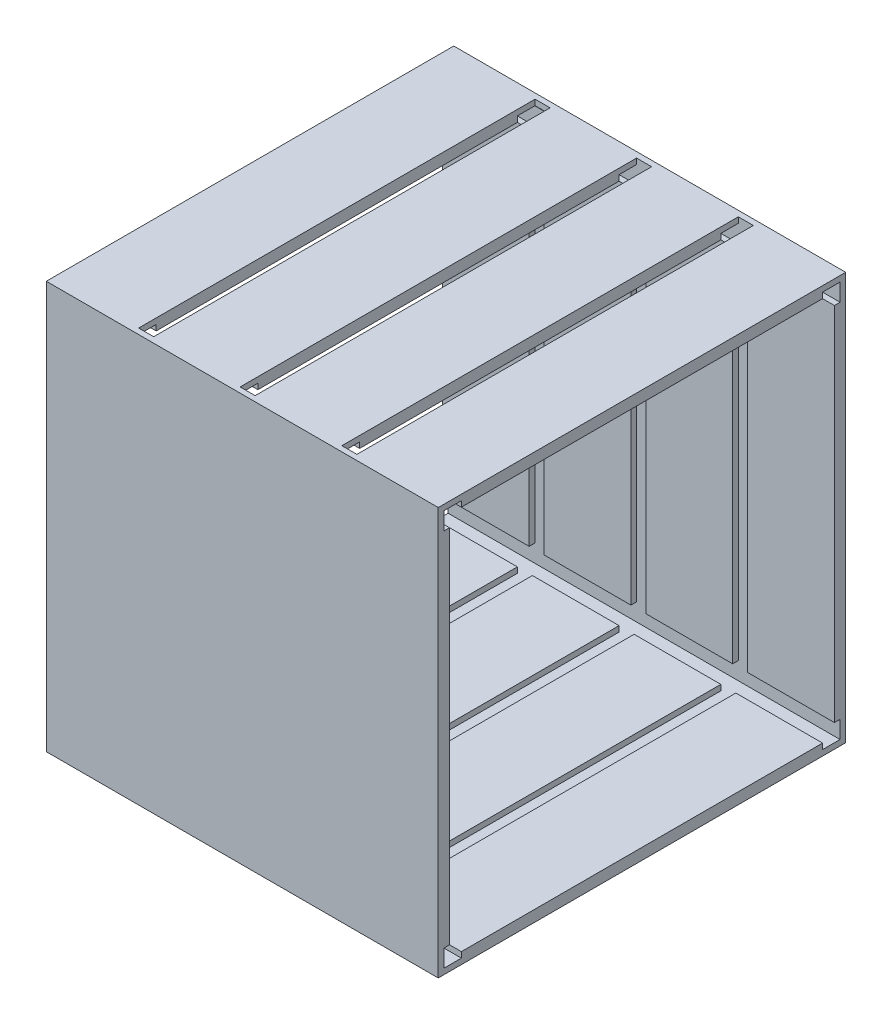
SolidWorks part; units mm, degrees
ref_plane "Front Plane" through (0, 0, 0) normal (0, 0, 1) x (1, 0, 0)
ref_plane "Top Plane" through (0, 0, 0) normal (0, 1, 0) x (1, 0, 0)
ref_plane "Right Plane" through (0, 0, 0) normal (1, 0, 0) x (0, 0, -1)
sketch "Sketch1" plane through (0, 0, 0) normal (1, 0, 0) x (0, 0, -1)
  line L1 (0, 0) -> (688.1, 0)
  line L2 (0, 0) -> (0, 688.1)
  line L3 (0, 688.1) -> (688.1, 688.1)
  line L4 (688.1, 0) -> (688.1, 688.1)
  line L5 (0, 0) -> (19.05, 0) construction
  line L6 (0, 0) -> (0, 19.05) construction
  line L7 (0, 19.05) -> (19.05, 19.05) construction
  line L8 (19.05, 0) -> (19.05, 19.05) construction
  line L9 (19.05, 19.05) -> (669.05, 19.05)
  line L10 (19.05, 19.05) -> (19.05, 669.05)
  line L11 (19.05, 669.05) -> (669.05, 669.05)
  line L12 (669.05, 19.05) -> (669.05, 669.05)
  dimension "D1" = 688.1
  dimension "D2" = 688.1
  dimension "D3" = 19.05
  dimension "D4" = 19.05
  dimension "D5" = 650
  dimension "D6" = 650
extrude "Boss-Extrude1" add sketch "Sketch1" along normal blind 661.9 contours L10 L11 L12 L9 | L2 L3 L4 L1
sketch "Sketch3" plane through (0, 0, -669.05) normal (0, 0, 1) x (1, 0, 0)
  line L1 (0, 669.05) -> (146.425, 669.05) construction
  line L2 (0, 669.05) -> (0, 19.05) construction
  line L3 (0, 19.05) -> (146.425, 19.05) construction
  line L4 (146.425, 669.05) -> (146.425, 19.05) construction
  line L5 (146.425, 669.05) -> (171.825, 669.05)
  line L6 (146.425, 669.05) -> (146.425, 19.05)
  line L7 (146.425, 19.05) -> (171.825, 19.05)
  line L8 (171.825, 669.05) -> (171.825, 19.05)
  line L9 (318.25, 669.05) -> (343.65, 669.05)
  line L10 (318.25, 669.05) -> (318.25, 19.05)
  line L11 (318.25, 19.05) -> (343.65, 19.05)
  line L12 (343.65, 669.05) -> (343.65, 19.05)
  line L13 (490.075, 669.05) -> (515.475, 669.05)
  line L14 (490.075, 669.05) -> (490.075, 19.05)
  line L15 (490.075, 19.05) -> (515.475, 19.05)
  line L16 (515.475, 669.05) -> (515.475, 19.05)
  line L17 (661.9, 688.1) -> (0, 688.1) construction
  point P15 (330.95, 669.05)
  dimension "D1" = 146.425
  dimension "D2" = 650
  dimension "D3" = 25.4
  dimension "D4" = 25.4
  dimension "D5" = 650
  dimension "D6" = 146.425
  dimension "D7" = 25.4
  dimension "D8" = 650
  dimension "D9" = 146.425
  dimension "D10" = 19.05
  dimension "D11" = 19.05
extrude "Cut-Extrude1" cut sketch "Sketch3" against normal blind 9.525
ref_plane "Plane1" through (0, 0, -344.05) normal (0, 0, -1) x (-1, 0, 0)
mirror "Mirror2" about plane through (0, 0, -344.05) normal (0, 0, -1) of "Cut-Extrude1"
ref_plane "Plane2" through (0, 344.05, 0) normal (0, 1, 0) x (1, 0, 0)
sketch "Sketch4" plane through (0, 19.05, 0) normal (0, 1, 0) x (1, 0, 0)
  line L0 (661.9, 688.1) -> (0, 688.1) construction
  line L1 (146.425, 678.575) -> (171.825, 678.575)
  line L2 (146.425, 678.575) -> (146.425, 9.075)
  line L3 (146.425, 9.075) -> (171.825, 9.075)
  line L4 (171.825, 678.575) -> (171.825, 9.075)
  line L5 (0, 0) -> (0, 688.1) construction
  line L6 (661.9, 0) -> (0, 0) construction
  line L7 (318.25, 678.575) -> (343.65, 678.575)
  line L8 (318.25, 678.575) -> (318.25, 9.075)
  line L9 (318.25, 9.075) -> (343.65, 9.075)
  line L10 (343.65, 678.575) -> (343.65, 9.075)
  line L11 (490.075, 678.575) -> (515.475, 678.575)
  line L12 (490.075, 678.575) -> (490.075, 9.525)
  line L13 (490.075, 9.525) -> (515.475, 9.525)
  line L14 (515.475, 678.575) -> (515.475, 9.525)
  dimension "D1" = 25.4
  dimension "D2" = 669.5
  dimension "D3" = 9.525
  dimension "D4" = 146.425
  dimension "D5" = 669.5
  dimension "D6" = 25.4
  dimension "D7" = 9.525
  dimension "D8" = 146.425
  dimension "D9" = 25.4
  dimension "D10" = 146.425
  dimension "D11" = 9.525
  dimension "D12" = 9.525
extrude "Cut-Extrude3" cut sketch "Sketch4" against normal blind 9.525
mirror "Mirror4" about plane through (0, 344.05, 0) normal (0, 1, 0) of "Cut-Extrude3"
sketch "Sketch6" plane through (0, 688.1, 0) normal (0, 1, 0) x (1, 0, 0)
  line L0 (0, 0) -> (0, 688.1) construction
  line L1 (146.425, 679.025) -> (171.825, 679.025)
  line L2 (146.425, 679.025) -> (146.425, 9.525)
  line L3 (146.425, 9.525) -> (171.825, 9.525)
  line L4 (171.825, 679.025) -> (171.825, 9.525)
  line L5 (318.25, 678.575) -> (343.65, 678.575)
  line L6 (318.25, 678.575) -> (318.25, 9.075)
  line L7 (318.25, 9.075) -> (343.65, 9.075)
  line L8 (343.65, 678.575) -> (343.65, 9.075)
  line L9 (490.075, 678.575) -> (515.475, 678.575)
  line L10 (490.075, 678.575) -> (490.075, 9.075)
  line L11 (490.075, 9.075) -> (515.475, 9.075)
  line L12 (515.475, 678.575) -> (515.475, 9.075)
  line L13 (661.9, 0) -> (0, 0) construction
  line L14 (661.9, 688.1) -> (0, 688.1) construction
  dimension "D1" = 669.5
  dimension "D2" = 25.4
  dimension "D3" = 146.425
  dimension "D4" = 9.525
  dimension "D5" = 25.4
  dimension "D6" = 669.5
  dimension "D7" = 9.525
  dimension "D8" = 146.425
  dimension "D9" = 25.4
  dimension "D10" = 669.5
  dimension "D11" = 9.525
  dimension "D12" = 146.425
extrude "Cut-Extrude4" cut sketch "Sketch6" against normal blind 9.525
sketch "Sketch7" plane through (0, 0, 0) normal (-1, 0, 0) x (0, 0, 1)
  line L0 (-19.05, 39.05) -> (-9.525, 39.05)
  line L1 (-19.05, 19.05) -> (-19.05, 669.05) construction
  line L2 (-9.525, 39.05) -> (-9.525, 9.525)
  line L3 (-9.525, 9.525) -> (-39.05, 9.525)
  line L4 (-39.05, 9.525) -> (-39.05, 19.05)
  line L5 (-19.05, 19.05) -> (-669.05, 19.05) construction
  line L6 (-39.05, 19.05) -> (-19.05, 19.05)
  line L7 (-19.05, 19.05) -> (-19.05, 39.05)
  dimension "D1" = 9.525
  dimension "D2" = 20
  dimension "D3" = 20
  dimension "D4" = 9.525
extrude "Cut-Extrude5" cut sketch "Sketch7" against normal blind 700
mirror "Mirror5" about plane through (0, 0, -344.05) normal (0, 0, -1) of "Cut-Extrude5"
mirror "Mirror6" about plane through (0, 344.05, 0) normal (0, 1, 0) of "Mirror5", "Cut-Extrude5"
